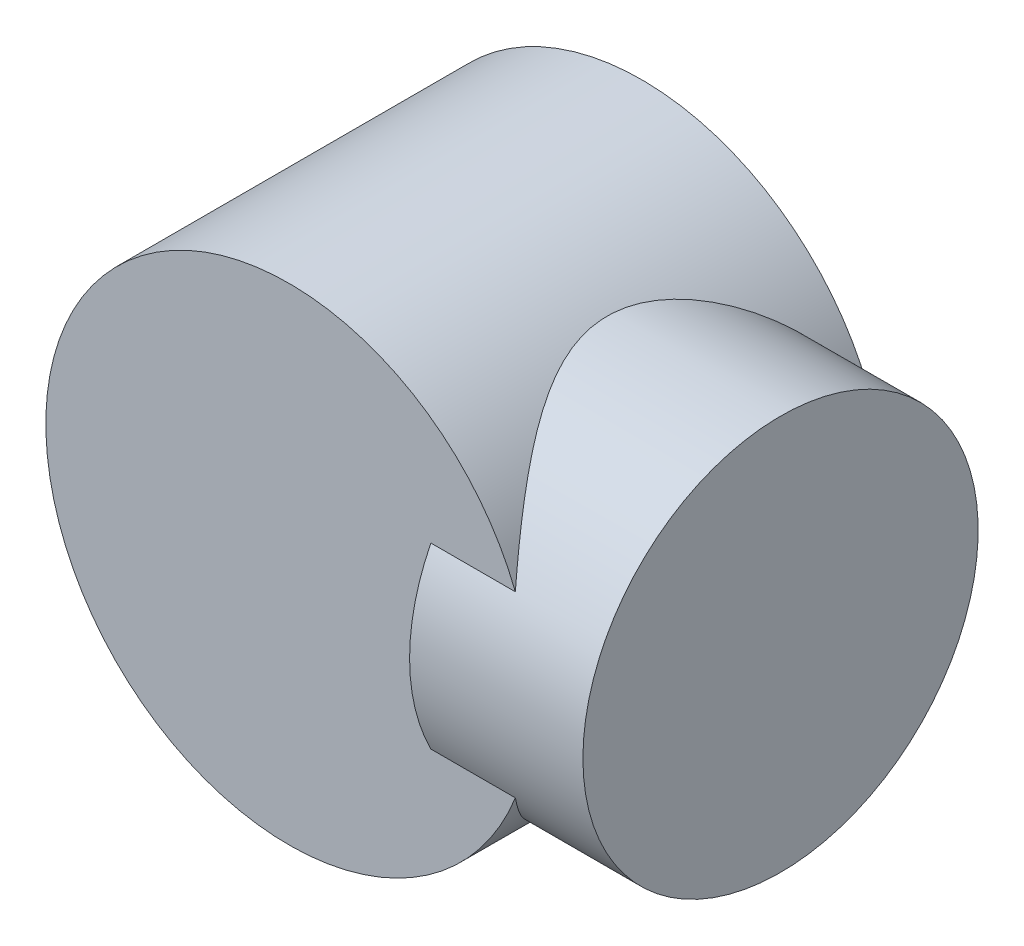
SolidWorks part; units mm, degrees
ref_plane "Piano frontale" through (0, 0, 0) normal (0, 0, 1) x (1, 0, 0)
ref_plane "Piano superiore" through (0, 0, 0) normal (0, 1, 0) x (1, 0, 0)
ref_plane "Piano destro" through (0, 0, 0) normal (1, 0, 0) x (0, 0, -1)
sketch "Schizzo2" plane through (0, 0, 0) normal (0, 0, 1) x (1, 0, 0)
  circle A0 centre (0, 0) radius 40
  dimension "D1" = 80
extrude "Base" add sketch "Schizzo2" along normal mid plane 58
sketch "Schizzo3" plane through (0, 0, 0) normal (0, 0, 1) x (1, 0, 0)
  line L0 (-78.4468, 0) -> (100.8014, 0) construction
  line L1 (40, 0) -> (51.8184, 0)
  line L2 (51.8184, 0) -> (51.8184, -32.5)
  line L3 (51.8184, -32.5) -> (23.3184, -32.5)
  circle A0 centre (0, 0) radius 40 construction
  arc A1 (23.3184, -32.5) -> (40, 0) centre (0, 0) ccw
  dimension "D1" = 32.5
  dimension "D2" = 28.5
revolve "Rivoluzione1" add sketch "Schizzo3" angle 360 about L0
